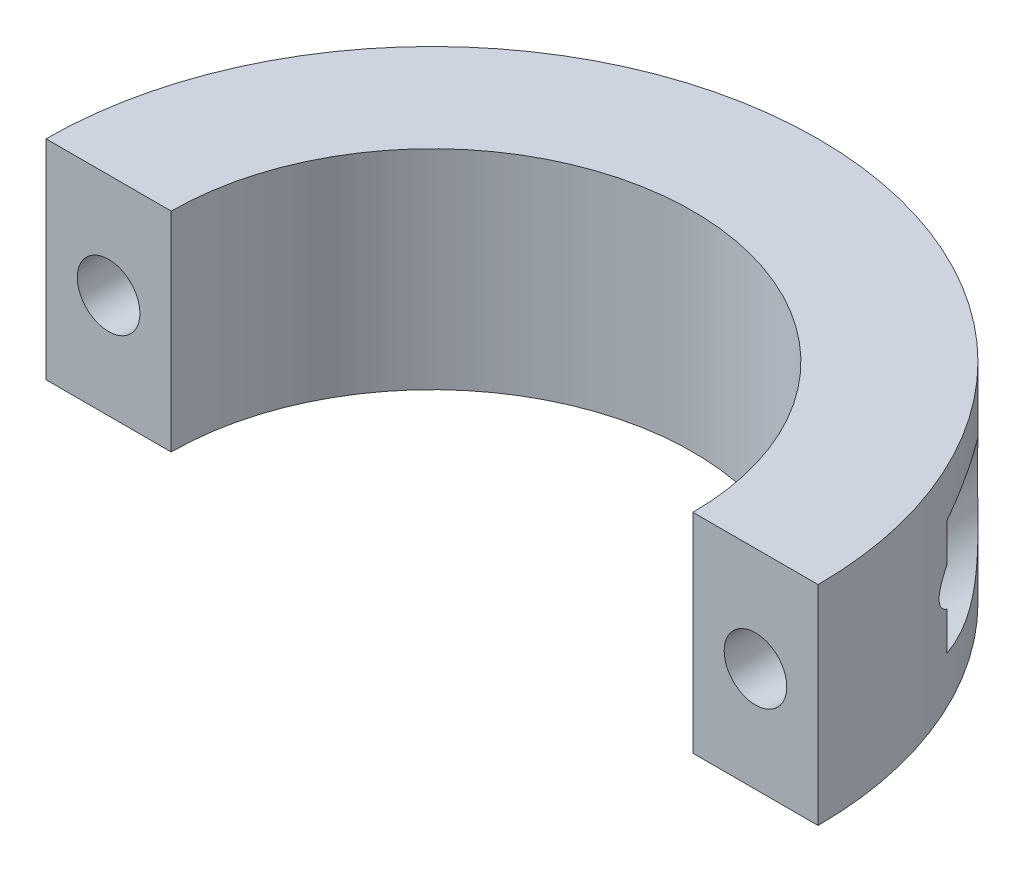
SolidWorks part; units mm, degrees
ref_plane "Front Plane" through (0, 0, 0) normal (0, 0, 1) x (1, 0, 0)
ref_plane "Top Plane" through (0, 0, 0) normal (0, 1, 0) x (1, 0, 0)
ref_plane "Right Plane" through (0, 0, 0) normal (1, 0, 0) x (0, 0, -1)
sketch "Sketch1" plane through (0, 0, 0) normal (0, 1, 0) x (1, 0, 0)
  line L0 (-18.5, 0) -> (18.5, 0)
  circle A0 centre (0, 0) radius 12.5
  circle A1 centre (0, 0) radius 18.5
  dimension "D1" = 25
  dimension "D2" = 37
extrude "Boss-Extrude1" add sketch "Sketch1" along normal blind 10 contours L0 A1 A0
sketch "Sketch2" plane through (0, 0, 0) normal (0, 0, 1) x (1, 0, 0)
  line L0 (-15.5, 10) -> (-15.5, 0)
  line L1 (-18.5, 10) -> (-12.5, 10) construction
  line L2 (-18.5, 0) -> (-12.5, 0) construction
  circle A0 centre (-15.5, 5) radius 1.5
  dimension "D1" = 3
extrude "Cut-Extrude1" cut sketch "Sketch2" against normal blind 8 contours A0
sketch "Sketch3" plane through (0, 0, -8) normal (0, 0, 1) x (1, 0, 0)
  circle A0 centre (-15.5, 5) radius 3
  dimension "D1" = 6
extrude "Cut-Extrude2" cut sketch "Sketch3" against normal through all
mirror "Mirror1" about plane through (0, 0, 0) normal (1, 0, 0) of "Cut-Extrude2", "Cut-Extrude1"
